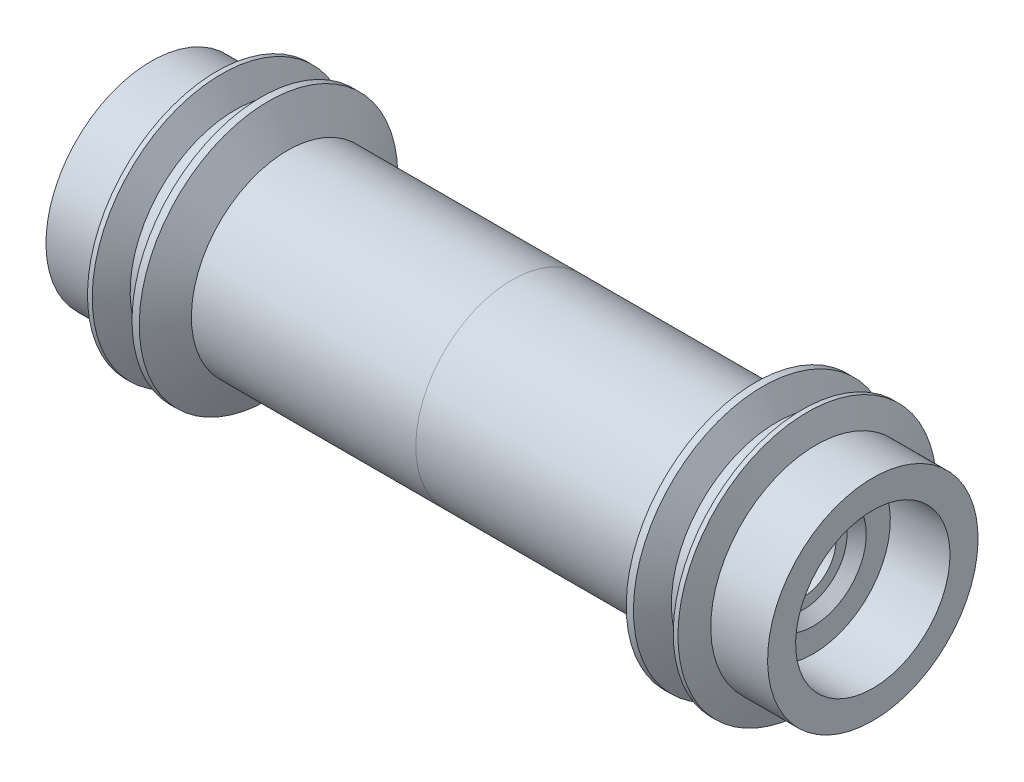
SolidWorks part; units mm, degrees
ref_plane "Front Plane" through (0, 0, 0) normal (0, 0, 1) x (1, 0, 0)
ref_plane "Top Plane" through (0, 0, 0) normal (0, 1, 0) x (1, 0, 0)
ref_plane "Right Plane" through (0, 0, 0) normal (1, 0, 0) x (0, 0, -1)
sketch "Sketch2" plane through (0, 0, 0) normal (0, 0, 1) x (1, 0, 0)
  line L0 (0, 0) -> (0, 28.4375) construction
  line L1 (-19.05, 4.075) -> (-15.9, 4.075) construction
  line L2 (-19.05, 4.075) -> (-19.05, -4.075) construction
  line L3 (-19.05, -4.075) -> (-15.9, -4.075) construction
  line L4 (-15.9, 4.075) -> (-15.9, -4.075) construction
  line L5 (-19.05, 4.075) -> (-15.9, -4.075) construction
  line L6 (-19.05, -4.075) -> (-15.9, 4.075) construction
  line L7 (15.9, 4.5) -> (47.6832, 4.5) construction
  line L8 (15.9, 4.5) -> (15.9, -4.5) construction
  line L9 (15.9, -4.5) -> (47.6832, -4.5) construction
  line L10 (47.6832, 4.5) -> (47.6832, -4.5) construction
  line L11 (15.9, 4.5) -> (47.6832, -4.5) construction
  line L12 (15.9, -4.5) -> (47.6832, 4.5) construction
  line L13 (-19.05, 0) -> (47.6832, 0) construction
  line L14 (-19.05, 5.5562) -> (-16.05, 5.5562)
  line L15 (-16.05, 5.5562) -> (-15.5878, 6.8262)
  line L16 (-15.5878, 6.8262) -> (-15.3382, 6.8262)
  line L19 (-13.2368, 6.8262) -> (-12.8558, 6.8262)
  line L20 (-12.8558, 6.8262) -> (-11.8476, 5.08)
  line L21 (-11.8476, 5.08) -> (0, 5.08)
  line L22 (-19.05, 5.5562) -> (-19.05, 4.075)
  line L23 (-19.05, 4.075) -> (-15.9, 4.075)
  line L24 (-15.9, 4.075) -> (-15.9, 0)
  line L25 (-15.9, 0) -> (0, 0)
  line L26 (0, 0) -> (0, 5.08)
  line L27 (-33.5594, -5.5562) -> (-33.5594, 5.5562) construction
  line L28 (-14.2875, 5.5562) -> (-14.2875, 7.68) construction
  line L29 (-14.2875, 5.5562) -> (14.2875, 5.5562) construction
  line L30 (-19.05, 5.5562) -> (19.05, 5.5562) construction
  line L31 (0, 1.6) -> (-6.5, 1.6)
  line L32 (-6.5, 1.6) -> (-8.1, 0)
  line L33 (-6.5, 1.6) -> (-6.5, -1.6) construction
  line L34 (-6.5, 1.6) -> (6.5, 1.6) construction
  line L35 (-15.9, 1.7145) -> (-9.225, 1.7145)
  line L36 (-9.225, 1.7145) -> (-9.225, 0)
  line L37 (-15.9, 2.805) -> (-15.392, 2.297)
  line L38 (-9.225, 1.7145) -> (-22.225, 1.7145) construction
  line L39 (-9.225, 1.7145) -> (-9.225, -1.7145) construction
  line L40 (-9.225, -1.7145) -> (-22.225, -1.7145) construction
  line L41 (-22.225, 1.7145) -> (-22.225, -1.7145) construction
  line L42 (-15.392, 2.297) -> (-15.392, 0)
  line L43 (-15.3382, 6.8262) -> (-14.605, 5.5562)
  line L44 (-14.605, 5.5562) -> (-13.97, 5.5562)
  line L45 (-13.97, 5.5562) -> (-13.2368, 6.8262)
  point P0 (-17.475, 0)
  point P5 (31.7916, 0)
  point P27 (-33.5594, 0)
  point P28 (-13.0463, 6.8262)
  point P29 (-6.5, 0)
  point P33 (0, 5.5562)
  point P36 (0, 1.6)
  point P48 (-9.225, 0)
  point P51 (0, 5.5562)
  point P54 (-14.2875, 5.5562)
  dimension "D1" = 3.15
  dimension "D3" = 5.08
  dimension "D4" = 11.1125
  dimension "D5" = 8.15
  dimension "D6" = 60
  dimension "D7" = 60
  dimension "D8" = 1.27
  dimension "D9" = 70
  dimension "D10" = 28.575
  dimension "D11" = 38.1
  dimension "D12" = 0.381
  dimension "D13" = 45
  dimension "D14" = 13
  dimension "D15" = 3.2
  dimension "D16" = 3.429
  dimension "D17" = 3.175
  dimension "D18" = 1.27
  dimension "D19" = 0.508
  dimension "D20" = 45
  dimension "D21" = 13
  dimension "D22" = 3
  dimension "D23" = 0.635
revolve "Revolve1" add sketch "Sketch2" angle 360 about L13
mirror "Mirror1" about plane through (0, 0, 0) normal (1, 0, 0) of bodies 101
chamfer "Chamfer1" distance 0.508 angle 45 1 edges at (-19.05, -4.075, 0)
